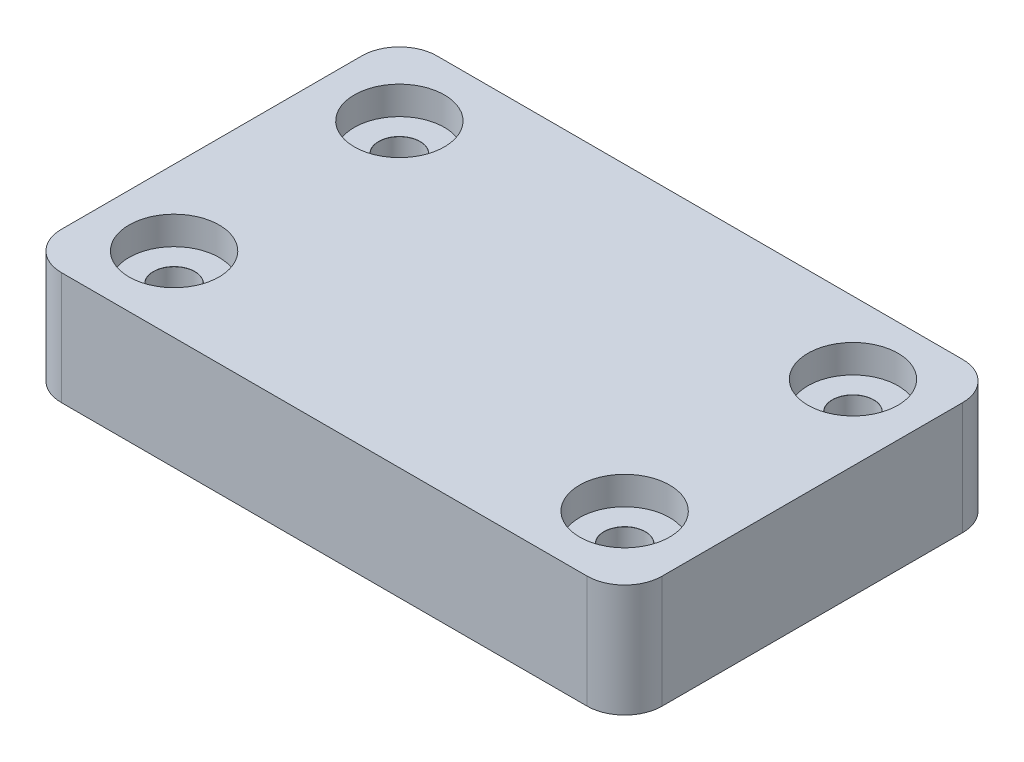
SolidWorks part; units mm, degrees
ref_plane "Alzado" through (0, 0, 0) normal (0, 0, 1) x (1, 0, 0)
ref_plane "Planta" through (0, 0, 0) normal (0, 1, 0) x (1, 0, 0)
ref_plane "Vista lateral" through (0, 0, 0) normal (1, 0, 0) x (0, 0, -1)
sketch "Croquis1" plane through (0, 0, 0) normal (0, 1, 0) x (1, 0, 0)
  line L1 (-70, -50) -> (70, -50)
  line L2 (-80, -40) -> (-80, 40)
  line L3 (-70, 50) -> (70, 50)
  line L4 (80, -40) -> (80, 40)
  line L5 (-80, -50) -> (80, 50) construction
  line L6 (-80, 50) -> (80, -50) construction
  arc A0 (-70, -50) -> (-80, -40) centre (-70, -40) cw
  arc A1 (80, -40) -> (70, -50) centre (70, -40) cw
  arc A2 (70, 50) -> (80, 40) centre (70, 40) cw
  arc A3 (-80, 40) -> (-70, 50) centre (-70, 40) cw
  point P0 (0, 0)
  dimension "D1" = 10
  dimension "D2" = 160
  dimension "D3" = 100
extrude "Saliente-Extruir1" add sketch "Croquis1" along normal blind 30
hole_wizard "Refrentado para tornillo con cabeza troncocónica de M101" positions "Croquis4" profile "Croquis5" counterbore size "M10" standard "Ansi Metric" end condition through all
sketch "Croquis4" plane through (0, 30, 0) normal (0, 1, 0) x (1, 0, 0)
  line L1 (0, 50) -> (0, 0) construction
  line L2 (70, 50) -> (-70, 50) construction
  line L3 (0, 0) -> (80, 0) construction
  line L4 (80, -40) -> (80, 40) construction
  point P0 (-60, 30)
  point P2 (60, 30.8174)
  point P17 (-60, -30)
  point P19 (60, -30)
  dimension "D1" = 60
  dimension "D2" = 60
  dimension "D3" = 30
  dimension "D4" = 30
  dimension "D5" = 30
  dimension "D6" = 60
  dimension "D7" = 60
sketch "Croquis5" plane through (-60, 30, -30) normal (1, 0, 0) x (0, 0, 1)
  line L0 (0, 0) -> (0, 30)
  line L1 (5.5, 29.975) -> (5.525, 30)
  line L2 (5.5, 29.975) -> (5.5, 7.525)
  line L3 (5.5, 7.525) -> (5.525, 7.5)
  line L4 (5.525, 7.5) -> (12, 7.5)
  line L5 (12, 7.5) -> (12, 0)
  line L7 (12, 0) -> (0, 0)
  line L9 (-5.5, 7.525) -> (-5.525, 7.5) construction
  line L11 (0, -6.35) -> (0, 107.95) construction
  line L12 (5.525, 30) -> (0, 30)
  line L13 (-5.5, 29.975) -> (-5.525, 30) construction
  dimension "Diámetro de taladro hasta el siguiente" = 11
  dimension "Profundidad de taladro hasta el siguiente" = 30
  dimension "Diámetro de refrentado" = 24
  dimension "Profundidad de refrentado" = 7.5
  dimension "Diámetro de avellanado de medio" = 11.05
  dimension "Ángulo de avellanado de medio" = 90
  dimension "Diámetro de avellanado lejano" = 11.05
  dimension "Ángulo de avellanado lejano" = 90
